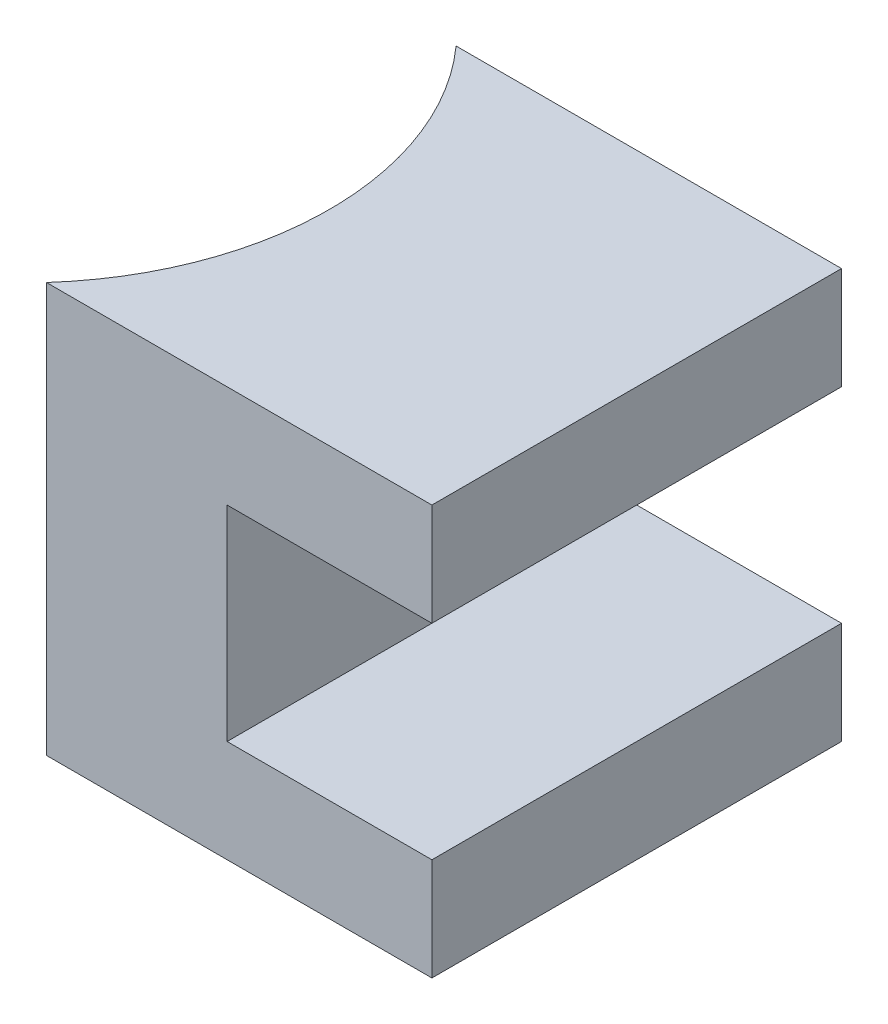
SolidWorks part; units mm, degrees
ref_plane "前视基准面" through (0, 0, 0) normal (0, 0, 1) x (1, 0, 0)
ref_plane "上视基准面" through (0, 0, 0) normal (0, 1, 0) x (1, 0, 0)
ref_plane "右视基准面" through (0, 0, 0) normal (1, 0, 0) x (0, 0, -1)
sketch "草图1" plane through (0, 0, 0) normal (0, 1, 0) x (1, 0, 0)
  line L0 (11.1803, 10) -> (30, 10)
  line L1 (30, 10) -> (30, -10)
  line L2 (30, -10) -> (11.1803, -10)
  circle A0 centre (0, 0) radius 15
  dimension "D1" = 30
  dimension "D2" = 20
  dimension "D3" = 10
  dimension "D4" = 30
sketch "草图2" plane through (0, 0, 0) normal (0, 1, 0) x (1, 0, 0)
  line L0 (11.1803, 10) -> (30, 10)
  line L1 (30, 10) -> (30, -10)
  line L2 (30, -10) -> (11.1803, -10)
  arc A0 (11.1803, -10) -> (11.1803, 10) centre (0, 0) ccw
extrude "凸台-拉伸1" add sketch "草图2" along normal mid plane 20
sketch "草图3" plane through (0, 0, 10) normal (0, 0, 1) x (1, 0, 0)
  line L0 (20, 5) -> (35.2084, 5)
  line L1 (35.2084, 5) -> (35.2084, -5)
  line L2 (35.2084, -5) -> (20, -5)
  line L3 (20, -5) -> (20, 5)
  line L4 (11.1803, 0) -> (30, 0) construction
  line L5 (30, 10) -> (30, -10) construction
  point P6 (20.5902, 0)
  dimension "D1" = 10
  dimension "D2" = 5
  dimension "D3" = 10
  dimension "D4" = 5.2084
extrude "切除-拉伸1" cut sketch "草图3" against normal through all both and the other way through all
